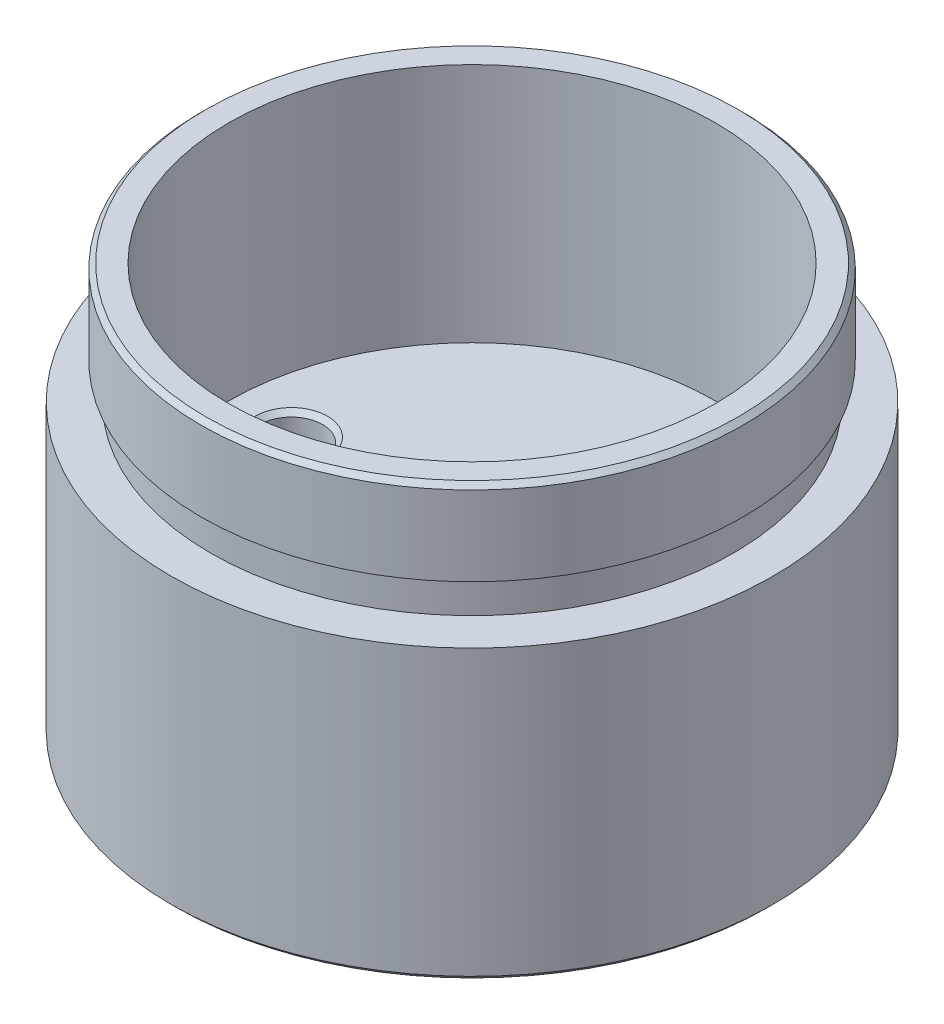
SolidWorks part; units mm, degrees
ref_plane "Front Plane" through (0, 0, 0) normal (0, 0, 1) x (1, 0, 0)
ref_plane "Top Plane" through (0, 0, 0) normal (0, 1, 0) x (1, 0, 0)
ref_plane "Right Plane" through (0, 0, 0) normal (1, 0, 0) x (0, 0, -1)
sketch "Sketch1" plane through (0, 0, 0) normal (0, 1, 0) x (1, 0, 0)
  circle A0 centre (0, 0) radius 12.5
extrude "Boss-Extrude1" add sketch "Sketch1" along normal blind 17
sketch "Sketch2" plane through (0, 17, 0) normal (0, 1, 0) x (1, 0, 0)
  circle A0 centre (0, 0) radius 10.1
extrude "Cut-Extrude1" cut sketch "Sketch2" against normal blind 10
sketch "Sketch3" plane through (0, 7, 0) normal (0, 1, 0) x (1, 0, 0)
  circle A0 centre (7.5, 0) radius 1.3
  circle A1 centre (-7.5, 0) radius 1.3
  dimension "D1" = 2.6
  dimension "D2" = 2.6
  dimension "D3" = 15
  dimension "D4" = 7.5
extrude "Cut-Extrude2" cut sketch "Sketch3" against normal blind 10
sketch "Sketch4" plane through (0, 17, 0) normal (0, 1, 0) x (1, 0, 0)
  circle A0 centre (0, 0) radius 10.85
  circle A1 centre (0, 0) radius 12.5
  dimension "D1" = 21.7
extrude "Cut-Extrude3" cut sketch "Sketch4" against normal blind 5
sketch "Sketch7" plane through (0, 17, 0) normal (0, 1, 0) x (1, 0, 0)
  circle A0 centre (0, 0) radius 10.85
  circle A1 centre (0, 0) radius 11.25
  dimension "D1" = 22.5
extrude "Boss-Extrude2" add sketch "Sketch7" against normal blind 3.5
cosmetic thread "Cosmetic Thread3" parameters "D1"=3.2999, "D2"=21.8
chamfer "Chamfer1" distance 0.2 angle 45 6 edges at (0, 0, 12.5) (0, 17, 11.25) (-7.5, 7, 1.3) (7.5, 7, 1.3) (7.5, 0, 1.3) (-7.5, 0, 1.3)
